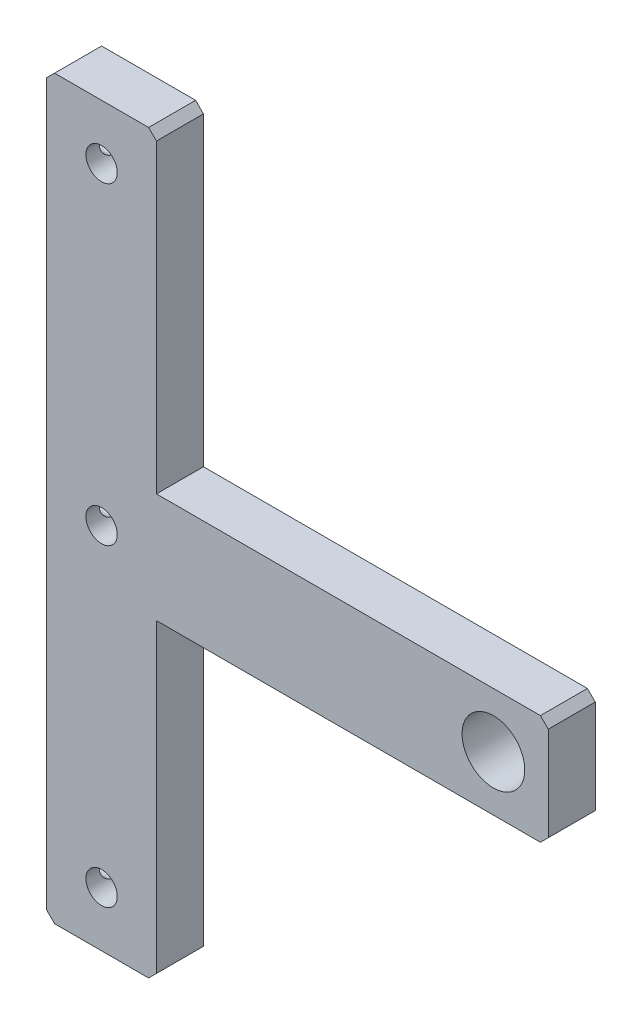
SolidWorks part; units mm, degrees
material "2024-T3"
ref_plane "正面" through (0, 0, 0) normal (0, 0, 1) x (1, 0, 0)
ref_plane "平面" through (0, 0, 0) normal (0, 1, 0) x (1, 0, 0)
ref_plane "右側面" through (0, 0, 0) normal (1, 0, 0) x (0, 0, -1)
sketch "ｽｹｯﾁ3" plane through (0, 0, 0) normal (0, 0, 1) x (1, 0, 0)
  line L0 (0, -47) -> (0, 47)
  line L1 (0, 47) -> (14, 47)
  line L2 (0, -47) -> (14, -47)
  line L3 (14, 47) -> (14, 7)
  line L4 (14, -47) -> (14, -7)
  line L5 (14, 7) -> (64, 7)
  line L6 (64, 7) -> (64, -7)
  line L7 (14, -7) -> (64, -7)
  point P4 (0, 0)
  dimension "D1" = 94
  dimension "D2" = 14
  dimension "D3" = 40
  dimension "D4" = 40
  dimension "D5" = 50
  dimension "D6" = 14
extrude "ﾎﾞｽ - 押し出し1" add sketch "ｽｹｯﾁ3" along normal blind 6
sketch "ｽｹｯﾁ4" plane through (0, 0, 6) normal (0, 0, 1) x (1, 0, 0)
  line L0 (14, 47) -> (0, 47) construction
  line L1 (0, 47) -> (0, -47) construction
  line L3 (64, 7) -> (14, 7) construction
  line L4 (64, -7) -> (64, 7) construction
  line L5 (14, -7) -> (64, -7) construction
  line L6 (14, -47) -> (14, -7) construction
  line L7 (0, -47) -> (14, -47) construction
  circle A0 centre (7, 40) radius 2
  circle A1 centre (7, -40) radius 2
  circle A2 centre (7, 0) radius 2
  circle A3 centre (57, 0) radius 4
  dimension "D1" = 4
  dimension "D3" = 7
  dimension "D4" = 4
  dimension "D8" = 8
  dimension "D10" = 4
  dimension "D2" = 7
  dimension "D5" = 7
  dimension "D6" = 7
  dimension "D7" = 7
  dimension "D9" = 7
  dimension "D11" = 7
  dimension "D12" = 7
extrude "ｶｯﾄ - 押し出し2" cut sketch "ｽｹｯﾁ4" against normal through all
sketch "ｽｹｯﾁ5" plane through (0, 0, 0) normal (-1, 0, 0) x (0, 0, 1)
  line L0 (6, -47) -> (0, -47) construction
  line L1 (6, 47) -> (6, -47) construction
  line L2 (6, 47) -> (0, 47) construction
  point P0 (3, -40)
  point P6 (3, 40)
  point P8 (3, 0)
  dimension "D1" = 7
  dimension "D2" = 3
  dimension "D3" = 3
  dimension "D4" = 7
  dimension "D5" = 3
  dimension "D6" = 40
hole_wizard "M3x0.5 ねじ穴1" positions "ｽｹｯﾁ5" profile "ｽｹｯﾁ6" tap size "M3x0.5" standard "JIS"
sketch "ｽｹｯﾁ6" plane through (0, -40, 3) normal (0, 1, 0) x (0, 0, 1)
  line L0 (0, 0) -> (0, 5)
  line L1 (0, 5) -> (1.25, 5)
  line L2 (1.25, 5) -> (1.25, 0)
  line L5 (1.25, 0) -> (0, 0)
  line L11 (0, -6.35) -> (0, 107.95) construction
  dimension "次ｻｰﾌｪｽまでのねじ下穴ﾄﾞﾘﾙ直径" = 2.5
  dimension "次ｻｰﾌｪｽまでのねじ下穴ﾄﾞﾘﾙの深さ" = 5
cosmetic thread "穴のねじ山1" parameters "D2"=3
cosmetic thread "穴のねじ山2" parameters "D2"=3
cosmetic thread "穴のねじ山3" parameters "D2"=3
chamfer "面取り1" distance 1 angle 45 6 edges at (0, -47, 3) (14, -47, 3) (64, -7, 3) (64, 7, 3) (14, 47, 3) (0, 47, 3)
